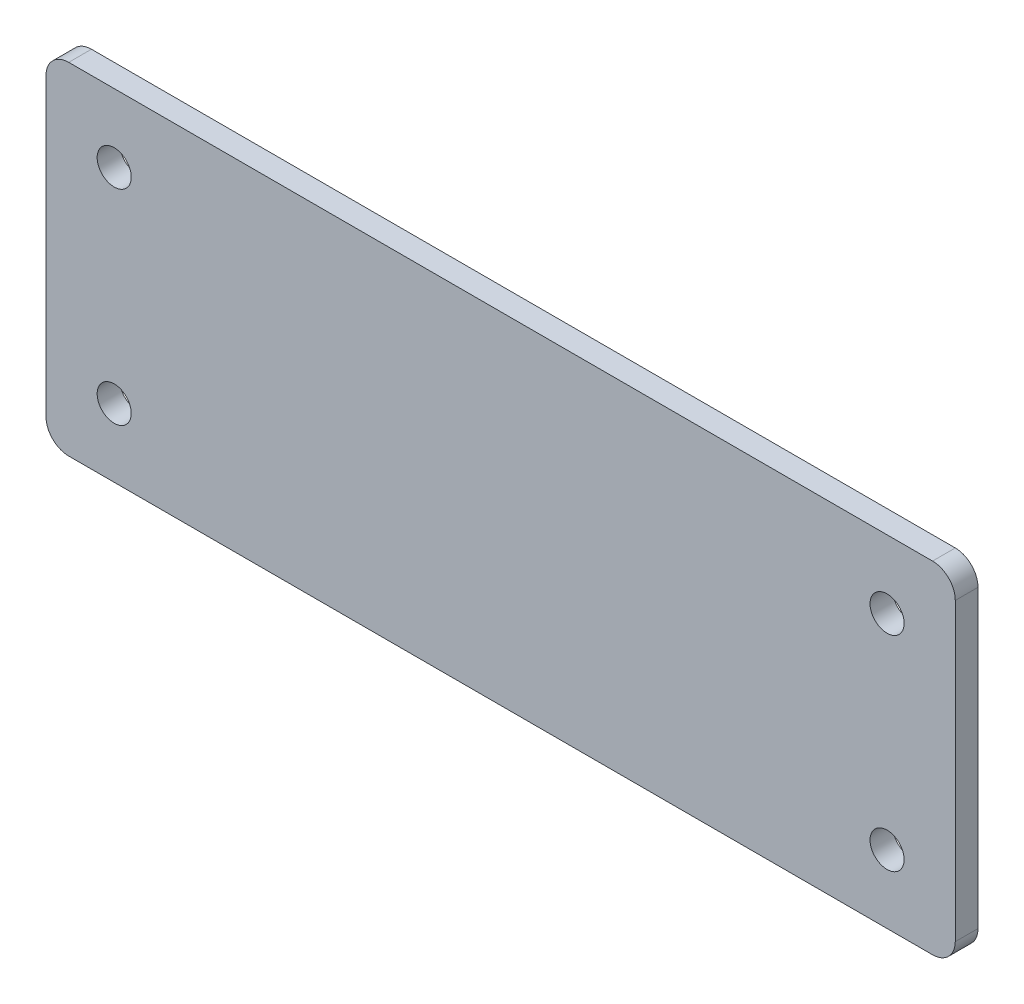
SolidWorks part; units mm, degrees
material "Сталь 3 ГОСТ 535-88"
ref_plane "Спереди" through (0, 0, 0) normal (0, 0, 1) x (1, 0, 0)
ref_plane "Сверху" through (0, 0, 0) normal (0, 1, 0) x (1, 0, 0)
ref_plane "Справа" through (0, 0, 0) normal (1, 0, 0) x (0, 0, -1)
sketch "Эскиз1" plane through (0, 0, 0) normal (0, 0, 1) x (1, 0, 0)
  line L1 (-200, -75) -> (200, -75)
  line L2 (-200, -75) -> (-200, 75)
  line L3 (-200, 75) -> (200, 75)
  line L4 (200, -75) -> (200, 75)
  line L5 (-200, -75) -> (200, 75) construction
  line L6 (-200, 75) -> (200, -75) construction
  point P0 (0, 0)
  dimension "D1" = 150
  dimension "D2" = 400
extrude "Бобышка-Вытянуть1" add sketch "Эскиз1" along normal mid plane 10
sketch "Эскиз2" plane through (0, 0, 5) normal (0, 0, 1) x (1, 0, 0)
  line L1 (-200, 75) -> (-200, -75) construction
  line L2 (200, 75) -> (-200, 75) construction
  line L3 (5.5, 0) -> (-5.5, 0) construction
  line L4 (0, -5.5) -> (0, 5.5) construction
  circle A0 centre (-170, 45) radius 7.5
  circle A1 centre (-170, -45) radius 7.5
  circle A2 centre (170, -45) radius 7.5
  circle A3 centre (170, 45) radius 7.5
  dimension "D1" = 15
  dimension "D2" = 30
  dimension "D3" = 30
extrude "Вырез-Вытянуть1" cut sketch "Эскиз2" against normal through all
fillet "Скругление1" radius 10 4 edges at (-200, 75, 0) (200, 75, 0) (200, -75, 0) (-200, -75, 0)
